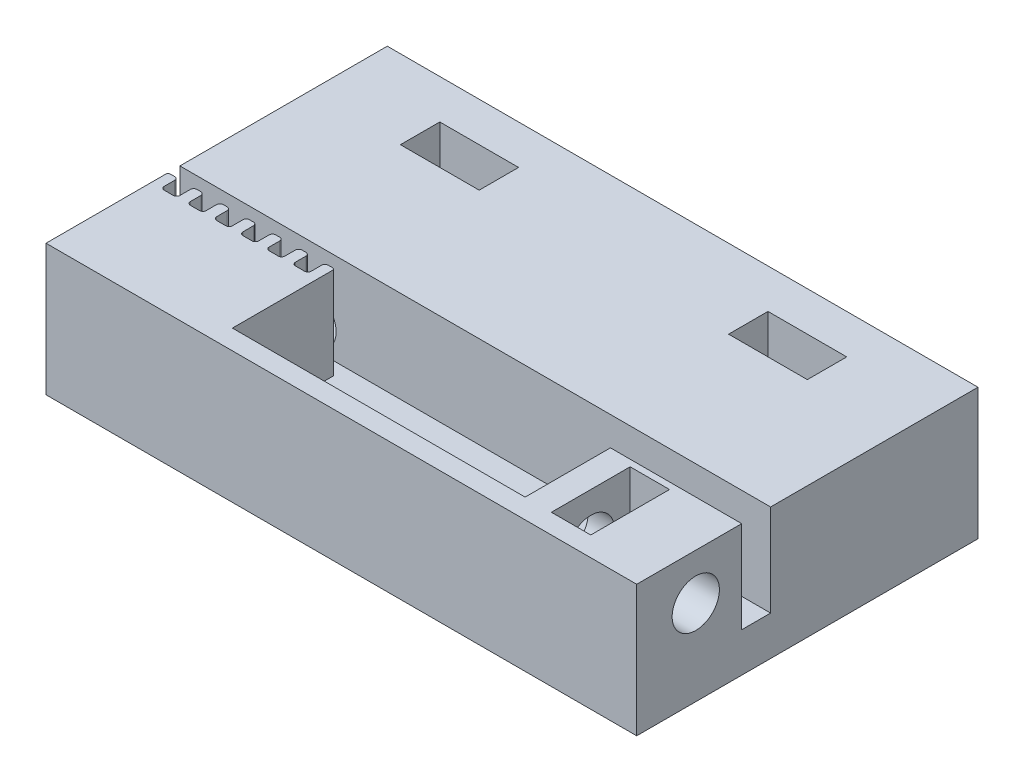
SolidWorks part; units mm, degrees
ref_plane "前视基准面" through (0, 0, 0) normal (0, 0, 1) x (1, 0, 0)
ref_plane "上视基准面" through (0, 0, 0) normal (0, 1, 0) x (1, 0, 0)
ref_plane "右视基准面" through (0, 0, 0) normal (1, 0, 0) x (0, 0, -1)
sketch "草图1" plane through (0, 0, 0) normal (0, 1, 0) x (1, 0, 0)
  line L1 (0, 0) -> (45, 0)
  line L2 (0, 0) -> (0, 26)
  line L3 (0, 26) -> (45, 26)
  line L4 (45, 0) -> (45, 26)
  dimension "D1" = 26
  dimension "D2" = 45
extrude "凸台-拉伸1" add sketch "草图1" along normal blind 10
sketch "草图3" plane through (0, 10, 0) normal (0, 1, 0) x (1, 0, 0)
  line L1 (44.35, 9.3) -> (44.35, 7.2991) construction
  line L3 (43, 8) -> (43.7, 8)
  line L4 (44.75, 8.25) -> (44.75, 9.05)
  line L5 (44.5, 9.3) -> (44.2, 9.3)
  line L6 (45, 0) -> (45, 26) construction
  line L7 (43.95, 8.25) -> (43.95, 9.05)
  line L8 (41, 8) -> (41.7, 8)
  line L9 (41.95, 8.25) -> (41.95, 9.05)
  line L10 (42.5, 9.3) -> (42.2, 9.3)
  line L11 (42.75, 8.25) -> (42.75, 9.05)
  line L12 (39, 8) -> (39.7, 8)
  line L13 (39.95, 8.25) -> (39.95, 9.05)
  line L14 (40.5, 9.3) -> (40.2, 9.3)
  line L15 (40.75, 8.25) -> (40.75, 9.05)
  line L16 (37, 8) -> (37.7, 8)
  line L17 (37.95, 8.25) -> (37.95, 9.05)
  line L18 (38.5, 9.3) -> (38.2, 9.3)
  line L19 (38.75, 8.25) -> (38.75, 9.05)
  line L20 (35, 8) -> (35.7, 8)
  line L21 (35.95, 8.25) -> (35.95, 9.05)
  line L22 (36.5, 9.3) -> (36.2, 9.3)
  line L23 (36.75, 8.25) -> (36.75, 9.05)
  line L24 (33, 8) -> (33.7, 8)
  line L25 (33.95, 8.25) -> (33.95, 9.05)
  line L26 (34.5, 9.3) -> (34.2, 9.3)
  line L27 (34.75, 8.25) -> (34.75, 9.05)
  line L28 (31, 8) -> (31.7, 8)
  line L29 (31.95, 8.25) -> (31.95, 9.05)
  line L30 (32.5, 9.3) -> (32.2, 9.3)
  line L31 (32.75, 8.25) -> (32.75, 9.05)
  line L32 (29, 8) -> (29.7, 8)
  line L33 (29.95, 8.25) -> (29.95, 9.05)
  line L34 (30.5, 9.3) -> (30.2, 9.3)
  line L35 (30.75, 8.25) -> (30.75, 9.05)
  line L36 (27, 8) -> (27.7, 8)
  line L37 (27.95, 8.25) -> (27.95, 9.05)
  line L38 (28.5, 9.3) -> (28.2, 9.3)
  line L39 (28.75, 8.25) -> (28.75, 9.05)
  line L40 (25, 8) -> (25.7, 8)
  line L41 (25.95, 8.25) -> (25.95, 9.05)
  line L42 (26.5, 9.3) -> (26.2, 9.3)
  line L43 (26.75, 8.25) -> (26.75, 9.05)
  line L44 (23, 8) -> (23.7, 8)
  line L45 (23.95, 8.25) -> (23.95, 9.05)
  line L46 (24.5, 9.3) -> (24.2, 9.3)
  line L47 (24.75, 8.25) -> (24.75, 9.05)
  line L48 (21, 8) -> (21.7, 8)
  line L49 (21.95, 8.25) -> (21.95, 9.05)
  line L50 (22.5, 9.3) -> (22.2, 9.3)
  line L51 (22.75, 8.25) -> (22.75, 9.05)
  line L52 (19, 8) -> (19.7, 8)
  line L53 (19.95, 8.25) -> (19.95, 9.05)
  line L54 (20.5, 9.3) -> (20.2, 9.3)
  line L55 (20.75, 8.25) -> (20.75, 9.05)
  line L56 (17, 8) -> (17.7, 8)
  line L57 (17.95, 8.25) -> (17.95, 9.05)
  line L58 (18.5, 9.3) -> (18.2, 9.3)
  line L59 (18.75, 8.25) -> (18.75, 9.05)
  line L60 (15, 8) -> (15.7, 8)
  line L61 (15.95, 8.25) -> (15.95, 9.05)
  line L62 (16.5, 9.3) -> (16.2, 9.3)
  line L63 (16.75, 8.25) -> (16.75, 9.05)
  line L64 (13, 8) -> (13.7, 8)
  line L65 (13.95, 8.25) -> (13.95, 9.05)
  line L66 (14.5, 9.3) -> (14.2, 9.3)
  line L67 (14.75, 8.25) -> (14.75, 9.05)
  line L68 (11, 8) -> (11.7, 8)
  line L69 (11.95, 8.25) -> (11.95, 9.05)
  line L70 (12.5, 9.3) -> (12.2, 9.3)
  line L71 (12.75, 8.25) -> (12.75, 9.05)
  line L72 (9, 8) -> (9.7, 8)
  line L73 (9.95, 8.25) -> (9.95, 9.05)
  line L74 (10.5, 9.3) -> (10.2, 9.3)
  line L75 (10.75, 8.25) -> (10.75, 9.05)
  line L76 (7, 8) -> (7.7, 8)
  line L77 (7.95, 8.25) -> (7.95, 9.05)
  line L78 (8.5, 9.3) -> (8.2, 9.3)
  line L79 (8.75, 8.25) -> (8.75, 9.05)
  line L80 (5, 8) -> (5.7, 8)
  line L81 (5.95, 8.25) -> (5.95, 9.05)
  line L82 (6.5, 9.3) -> (6.2, 9.3)
  line L83 (6.75, 8.25) -> (6.75, 9.05)
  line L84 (3, 8) -> (3.7, 8)
  line L85 (3.95, 8.25) -> (3.95, 9.05)
  line L86 (4.5, 9.3) -> (4.2, 9.3)
  line L87 (4.75, 8.25) -> (4.75, 9.05)
  line L88 (1, 8) -> (1.7, 8)
  line L89 (1.95, 8.25) -> (1.95, 9.05)
  line L90 (2.5, 9.3) -> (2.2, 9.3)
  line L91 (2.75, 8.25) -> (2.75, 9.05)
  line L92 (0, 10.2) -> (0, 9.2)
  line L94 (0.5, 9.3) -> (0.2, 9.3)
  line L95 (0.75, 8.25) -> (0.75, 9.05)
  line L96 (0, 10.2) -> (45, 10.2)
  line L97 (0, 26) -> (0, 0) construction
  line L98 (45, 8) -> (45, 10.2)
  line L101 (-0.05, 8.25) -> (-0.05, 9.05) [skipped]
  line L102 (-1, 8) -> (-0.3, 8) [skipped]
  arc A0 (45, 8) -> (44.75, 8.25) centre (45, 8.25) cw
  arc A1 (44.75, 9.05) -> (44.5, 9.3) centre (44.5, 9.05) ccw
  arc A2 (43.7, 8) -> (43.95, 8.25) centre (43.7, 8.25) ccw
  arc A3 (43.95, 9.05) -> (44.2, 9.3) centre (44.2, 9.05) cw
  arc A4 (41.7, 8) -> (41.95, 8.25) centre (41.7, 8.25) ccw
  arc A5 (41.95, 9.05) -> (42.2, 9.3) centre (42.2, 9.05) cw
  arc A6 (42.75, 9.05) -> (42.5, 9.3) centre (42.5, 9.05) ccw
  arc A7 (43, 8) -> (42.75, 8.25) centre (43, 8.25) cw
  arc A8 (39.7, 8) -> (39.95, 8.25) centre (39.7, 8.25) ccw
  arc A9 (39.95, 9.05) -> (40.2, 9.3) centre (40.2, 9.05) cw
  arc A10 (40.75, 9.05) -> (40.5, 9.3) centre (40.5, 9.05) ccw
  arc A11 (41, 8) -> (40.75, 8.25) centre (41, 8.25) cw
  arc A12 (37.7, 8) -> (37.95, 8.25) centre (37.7, 8.25) ccw
  arc A13 (37.95, 9.05) -> (38.2, 9.3) centre (38.2, 9.05) cw
  arc A14 (38.75, 9.05) -> (38.5, 9.3) centre (38.5, 9.05) ccw
  arc A15 (39, 8) -> (38.75, 8.25) centre (39, 8.25) cw
  arc A16 (35.7, 8) -> (35.95, 8.25) centre (35.7, 8.25) ccw
  arc A17 (35.95, 9.05) -> (36.2, 9.3) centre (36.2, 9.05) cw
  arc A18 (36.75, 9.05) -> (36.5, 9.3) centre (36.5, 9.05) ccw
  arc A19 (37, 8) -> (36.75, 8.25) centre (37, 8.25) cw
  arc A20 (33.7, 8) -> (33.95, 8.25) centre (33.7, 8.25) ccw
  arc A21 (33.95, 9.05) -> (34.2, 9.3) centre (34.2, 9.05) cw
  arc A22 (34.75, 9.05) -> (34.5, 9.3) centre (34.5, 9.05) ccw
  arc A23 (35, 8) -> (34.75, 8.25) centre (35, 8.25) cw
  arc A24 (31.7, 8) -> (31.95, 8.25) centre (31.7, 8.25) ccw
  arc A25 (31.95, 9.05) -> (32.2, 9.3) centre (32.2, 9.05) cw
  arc A26 (32.75, 9.05) -> (32.5, 9.3) centre (32.5, 9.05) ccw
  arc A27 (33, 8) -> (32.75, 8.25) centre (33, 8.25) cw
  arc A28 (29.7, 8) -> (29.95, 8.25) centre (29.7, 8.25) ccw
  arc A29 (29.95, 9.05) -> (30.2, 9.3) centre (30.2, 9.05) cw
  arc A30 (30.75, 9.05) -> (30.5, 9.3) centre (30.5, 9.05) ccw
  arc A31 (31, 8) -> (30.75, 8.25) centre (31, 8.25) cw
  arc A32 (27.7, 8) -> (27.95, 8.25) centre (27.7, 8.25) ccw
  arc A33 (27.95, 9.05) -> (28.2, 9.3) centre (28.2, 9.05) cw
  arc A34 (28.75, 9.05) -> (28.5, 9.3) centre (28.5, 9.05) ccw
  arc A35 (29, 8) -> (28.75, 8.25) centre (29, 8.25) cw
  arc A36 (25.7, 8) -> (25.95, 8.25) centre (25.7, 8.25) ccw
  arc A37 (25.95, 9.05) -> (26.2, 9.3) centre (26.2, 9.05) cw
  arc A38 (26.75, 9.05) -> (26.5, 9.3) centre (26.5, 9.05) ccw
  arc A39 (27, 8) -> (26.75, 8.25) centre (27, 8.25) cw
  arc A40 (23.7, 8) -> (23.95, 8.25) centre (23.7, 8.25) ccw
  arc A41 (23.95, 9.05) -> (24.2, 9.3) centre (24.2, 9.05) cw
  arc A42 (24.75, 9.05) -> (24.5, 9.3) centre (24.5, 9.05) ccw
  arc A43 (25, 8) -> (24.75, 8.25) centre (25, 8.25) cw
  arc A44 (21.7, 8) -> (21.95, 8.25) centre (21.7, 8.25) ccw
  arc A45 (21.95, 9.05) -> (22.2, 9.3) centre (22.2, 9.05) cw
  arc A46 (22.75, 9.05) -> (22.5, 9.3) centre (22.5, 9.05) ccw
  arc A47 (23, 8) -> (22.75, 8.25) centre (23, 8.25) cw
  arc A48 (19.7, 8) -> (19.95, 8.25) centre (19.7, 8.25) ccw
  arc A49 (19.95, 9.05) -> (20.2, 9.3) centre (20.2, 9.05) cw
  arc A50 (20.75, 9.05) -> (20.5, 9.3) centre (20.5, 9.05) ccw
  arc A51 (21, 8) -> (20.75, 8.25) centre (21, 8.25) cw
  arc A52 (17.7, 8) -> (17.95, 8.25) centre (17.7, 8.25) ccw
  arc A53 (17.95, 9.05) -> (18.2, 9.3) centre (18.2, 9.05) cw
  arc A54 (18.75, 9.05) -> (18.5, 9.3) centre (18.5, 9.05) ccw
  arc A55 (19, 8) -> (18.75, 8.25) centre (19, 8.25) cw
  arc A56 (15.7, 8) -> (15.95, 8.25) centre (15.7, 8.25) ccw
  arc A57 (15.95, 9.05) -> (16.2, 9.3) centre (16.2, 9.05) cw
  arc A58 (16.75, 9.05) -> (16.5, 9.3) centre (16.5, 9.05) ccw
  arc A59 (17, 8) -> (16.75, 8.25) centre (17, 8.25) cw
  arc A60 (13.7, 8) -> (13.95, 8.25) centre (13.7, 8.25) ccw
  arc A61 (13.95, 9.05) -> (14.2, 9.3) centre (14.2, 9.05) cw
  arc A62 (14.75, 9.05) -> (14.5, 9.3) centre (14.5, 9.05) ccw
  arc A63 (15, 8) -> (14.75, 8.25) centre (15, 8.25) cw
  arc A64 (11.7, 8) -> (11.95, 8.25) centre (11.7, 8.25) ccw
  arc A65 (11.95, 9.05) -> (12.2, 9.3) centre (12.2, 9.05) cw
  arc A66 (12.75, 9.05) -> (12.5, 9.3) centre (12.5, 9.05) ccw
  arc A67 (13, 8) -> (12.75, 8.25) centre (13, 8.25) cw
  arc A68 (9.7, 8) -> (9.95, 8.25) centre (9.7, 8.25) ccw
  arc A69 (9.95, 9.05) -> (10.2, 9.3) centre (10.2, 9.05) cw
  arc A70 (10.75, 9.05) -> (10.5, 9.3) centre (10.5, 9.05) ccw
  arc A71 (11, 8) -> (10.75, 8.25) centre (11, 8.25) cw
  arc A72 (7.7, 8) -> (7.95, 8.25) centre (7.7, 8.25) ccw
  arc A73 (7.95, 9.05) -> (8.2, 9.3) centre (8.2, 9.05) cw
  arc A74 (8.75, 9.05) -> (8.5, 9.3) centre (8.5, 9.05) ccw
  arc A75 (9, 8) -> (8.75, 8.25) centre (9, 8.25) cw
  arc A76 (5.7, 8) -> (5.95, 8.25) centre (5.7, 8.25) ccw
  arc A77 (5.95, 9.05) -> (6.2, 9.3) centre (6.2, 9.05) cw
  arc A78 (6.75, 9.05) -> (6.5, 9.3) centre (6.5, 9.05) ccw
  arc A79 (7, 8) -> (6.75, 8.25) centre (7, 8.25) cw
  arc A80 (3.7, 8) -> (3.95, 8.25) centre (3.7, 8.25) ccw
  arc A81 (3.95, 9.05) -> (4.2, 9.3) centre (4.2, 9.05) cw
  arc A82 (4.75, 9.05) -> (4.5, 9.3) centre (4.5, 9.05) ccw
  arc A83 (5, 8) -> (4.75, 8.25) centre (5, 8.25) cw
  arc A84 (1.7, 8) -> (1.95, 8.25) centre (1.7, 8.25) ccw
  arc A85 (1.95, 9.05) -> (2.2, 9.3) centre (2.2, 9.05) cw
  arc A86 (2.75, 9.05) -> (2.5, 9.3) centre (2.5, 9.05) ccw
  arc A87 (3, 8) -> (2.75, 8.25) centre (3, 8.25) cw
  arc A89 (0, 9.2) -> (0.2, 9.3) centre (0.2, 9.05) cw
  arc A90 (0.75, 9.05) -> (0.5, 9.3) centre (0.5, 9.05) ccw
  arc A91 (1, 8) -> (0.75, 8.25) centre (1, 8.25) cw
  arc A92 (-0.3, 8) -> (-0.05, 8.25) centre (-0.3, 8.25) ccw [skipped]
  dimension "D2" = 2
  dimension "D4" = 0.25
  dimension "D5" = 0.25
  dimension "D1" = 0
  dimension "D3" = 23
  dimension "D6" = 0.8
  dimension "D7" = 0.9
extrude "切除-拉伸1" cut sketch "草图3" against normal blind 7
sketch "草图4" plane through (0, 10, 0) normal (0, 1, 0) x (1, 0, 0)
  line L1 (45, 8) -> (15, 8)
  line L2 (45, 8) -> (45, 9.4)
  line L3 (45, 9.4) -> (15, 9.4)
  line L4 (15, 8) -> (15, 9.4)
  dimension "D1" = 1.4
  dimension "D2" = 30
extrude "切除-拉伸3" cut sketch "草图4" against normal blind 7
sketch "草图5" plane through (45, 0, 0) normal (1, 0, 0) x (0, 0, -1)
  line L0 (8, 6.5) -> (0, 6.5) construction
  line L1 (8, 3) -> (8, 10) construction
  line L2 (0, 10) -> (0, 0) construction
  line L3 (4.5, 10) -> (4.5, 0) construction
  line L4 (0, 10) -> (8, 10) construction
  line L5 (0, 0) -> (26, 0) construction
  circle A0 centre (4.5, 6.5) radius 1.8
  dimension "D3" = 3.6
  dimension "D1" = 3.5
  dimension "D2" = 3.5
extrude "切除-拉伸4" cut sketch "草图5" against normal blind 30
sketch "草图6" plane through (0, 10, 0) normal (0, 1, 0) x (1, 0, 0)
  line L0 (45, 4.5) -> (25.0035, 4.5) construction
  line L1 (45, 0) -> (45, 8) construction
  line L2 (15, 8) -> (45, 8) construction
  line L4 (37, 7.5) -> (40, 7.5)
  line L5 (37, 7.5) -> (37, 1.5)
  line L6 (37, 1.5) -> (40, 1.5)
  line L7 (40, 7.5) -> (40, 1.5)
  dimension "D1" = 3.5
  dimension "D2" = 5
  dimension "D3" = 3
  dimension "D4" = 6
  dimension "D5" = 3
extrude "切除-拉伸5" cut sketch "草图6" against normal blind 6.5
sketch "草图7" plane through (0, 10, 0) normal (0, 1, 0) x (1, 0, 0)
  line L0 (37, 7.5) -> (37, 1.5) construction
  line L1 (35, 1.5) -> (12.7, 1.5)
  line L2 (35, 1.5) -> (35, 9.613)
  line L3 (35, 9.613) -> (12.7, 9.613)
  line L4 (12.7, 1.5) -> (12.7, 9.613)
  line L5 (0, 0) -> (45, 0) construction
  dimension "D1" = 2
  dimension "D2" = 22.3
  dimension "D3" = 1.5
extrude "切除-拉伸7" cut sketch "草图7" against normal blind 7
sketch "草图8" plane through (0, 0, -26) normal (0, 0, -1) x (-1, 0, 0)
  line L0 (0, 5) -> (-45, 5) construction
  line L1 (0, 10) -> (0, 0) construction
  line L2 (-45, 10) -> (-45, 0) construction
  line L3 (-22.5, 0) -> (-22.5, 10) construction
  line L4 (-45, 0) -> (0, 0) construction
  line L5 (-45, 10) -> (0, 10) construction
  circle A0 centre (-10, 5) radius 1.9
  circle A1 centre (-35, 5) radius 1.9
  dimension "D1" = 3.8
  dimension "D2" = 12.5
extrude "切除-拉伸8" cut sketch "草图8" against normal blind 15.9
sketch "草图9" plane through (0, 10, 0) normal (0, 1, 0) x (1, 0, 0)
  line L0 (22.5, 26) -> (22.5, 10.2) construction
  line L1 (45, 26) -> (0, 26) construction
  line L2 (45, 10.2) -> (0, 10.2) construction
sketch "草图10" plane through (0, 10, 0) normal (0, 1, 0) x (1, 0, 0)
  line L0 (22.5, 26) -> (22.5, 10.2) construction
  line L1 (7, 23) -> (13, 23)
  line L2 (7, 23) -> (7, 20)
  line L3 (7, 20) -> (13, 20)
  line L4 (13, 23) -> (13, 20)
  line L7 (22.5, 26) -> (22.5, 10.2) construction
  line L8 (38, 23) -> (38, 20)
  line L9 (38, 20) -> (32, 20)
  line L10 (32, 23) -> (32, 20)
  line L11 (38, 23) -> (32, 23)
  line L12 (45, 26) -> (0, 26) construction
  dimension "D1" = 6
  dimension "D2" = 3
  dimension "D3" = 9.5
  dimension "D4" = 3
extrude "切除-拉伸9" cut sketch "草图10" against normal blind 8.5
